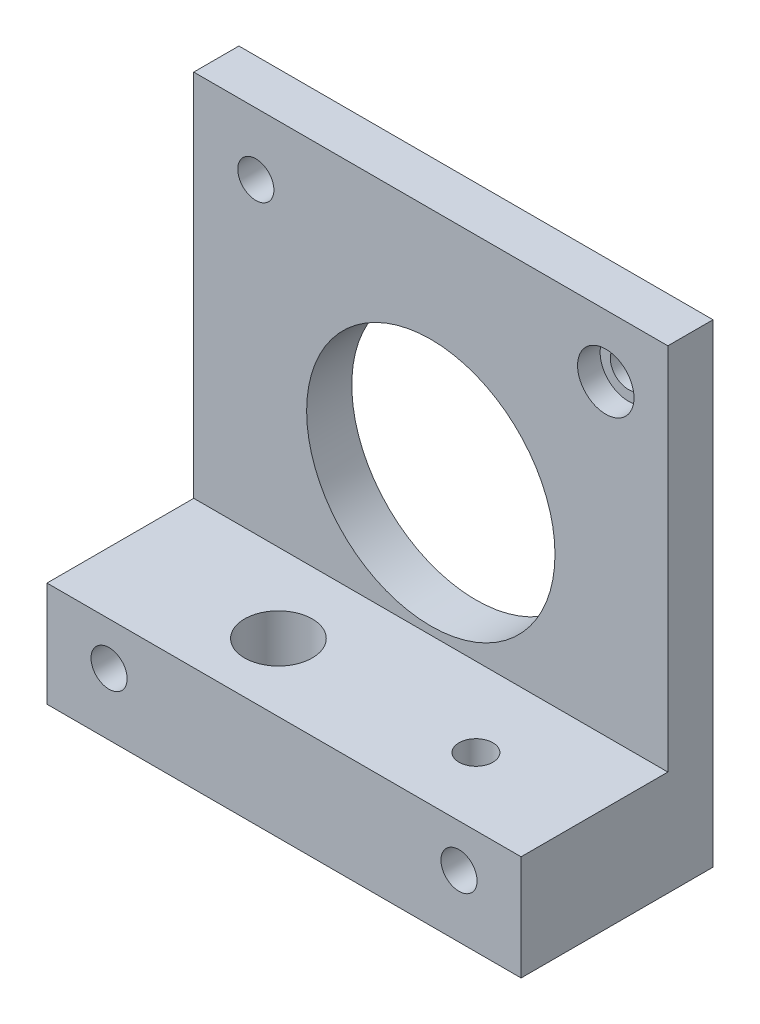
SolidWorks part; units mm, degrees
ref_plane "Front Plane" through (0, 0, 0) normal (0, 0, 1) x (1, 0, 0)
ref_plane "Top Plane" through (0, 0, 0) normal (0, 1, 0) x (1, 0, 0)
ref_plane "Right Plane" through (0, 0, 0) normal (1, 0, 0) x (0, 0, -1)
sketch "Sketch1" plane through (0, 0, 0) normal (0, 0, 1) x (1, 0, 0)
  line L1 (0, 0) -> (42, 0)
  line L2 (0, 0) -> (0, 42)
  line L3 (0, 42) -> (42, 42)
  line L4 (42, 0) -> (42, 42)
  dimension "D1" = 42
  dimension "D2" = 42
extrude "Boss-Extrude1" add sketch "Sketch1" along normal blind 17
sketch "Sketch3" plane through (0, 42, 0) normal (0, 1, 0) x (1, 0, 0)
  line L0 (42, -17) -> (42, 0) construction
  line L1 (0, -17) -> (42, -17)
  line L2 (0, -17) -> (0, -4)
  line L3 (0, -4) -> (42, -4)
  line L4 (42, -17) -> (42, -4)
  dimension "D1" = 13
extrude "Cut-Extrude1" cut sketch "Sketch3" against normal blind 32.7
sketch "Sketch4" plane through (0, 0, 4) normal (0, 0, 1) x (1, 0, 0)
  line L0 (42, 42) -> (0, 42) construction
  line L3 (42, 9.3) -> (42, 42) construction
  line L4 (0, 9.3) -> (0, 42) construction
  line L7 (0, 9.3) -> (0, 0) construction
  line L8 (0, 0) -> (42, 0) construction
  line L9 (42, 0) -> (42, 9.3) construction
  circle A0 centre (36.5, 36.5) radius 1.6
  circle A1 centre (5.5, 36.5) radius 1.6
  circle A2 centre (21, 21) radius 11
  circle A3 centre (5.5, 5.5) radius 1.6
  circle A4 centre (36.5, 5.5) radius 1.6
  dimension "D5" = 3.2
  dimension "D6" = 3.2
  dimension "D9" = 22
  dimension "D14" = 3.2
  dimension "D15" = 3.2
  dimension "D1" = 5.5
  dimension "D2" = 5.5
  dimension "D3" = 5.5
  dimension "D4" = 5.5
  dimension "D7" = 21
  dimension "D8" = 21
  dimension "D10" = 5.5
  dimension "D11" = 5.5
  dimension "D12" = 5.5
  dimension "D13" = 5.5
extrude "Cut-Extrude2" cut sketch "Sketch4" against normal through all and the other way through all
sketch "Sketch5" plane through (0, 0, 4) normal (0, 0, 1) x (1, 0, 0)
  circle A0 centre (36.5, 36.5) radius 2.5
  dimension "D1" = 5
extrude "Cut-Extrude3" cut sketch "Sketch5" against normal blind 2
sketch "Sketch6" plane through (0, 9.3, 0) normal (0, 1, 0) x (1, 0, 0)
  line L0 (42, -17) -> (42, -4) construction
  line L1 (0, -17) -> (42, -17) construction
  line L2 (0, -4) -> (0, -17) construction
  circle A0 centre (32, -11) radius 1.5
  circle A1 centre (14.5, -11) radius 3
  dimension "D2" = 3
  dimension "D6" = 6
  dimension "D1" = 10
  dimension "D3" = 6
  dimension "D4" = 14.5
  dimension "D5" = 6
extrude "Cut-Extrude4" cut sketch "Sketch6" against normal through all
